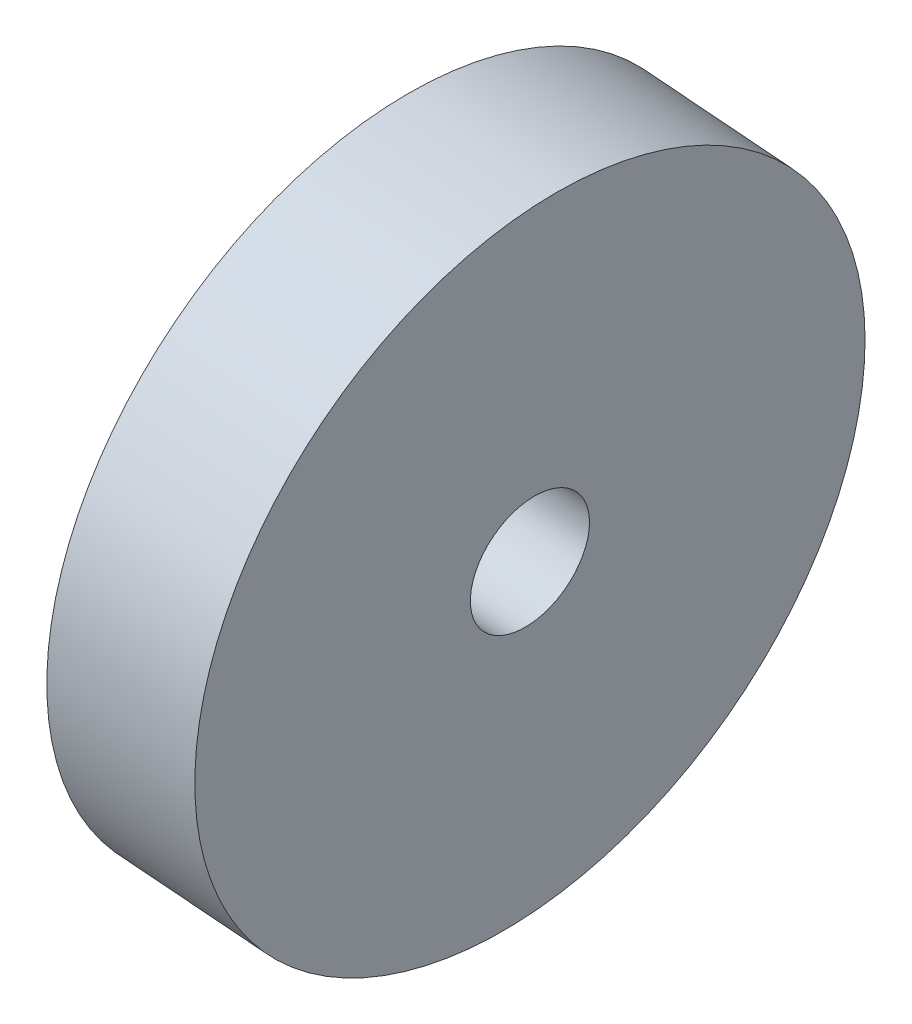
SolidWorks part; units mm, degrees
ref_plane "Front Plane" through (0, 0, 0) normal (0, 0, 1) x (1, 0, 0)
ref_plane "Top Plane" through (0, 0, 0) normal (0, 1, 0) x (1, 0, 0)
ref_plane "Right Plane" through (0, 0, 0) normal (1, 0, 0) x (0, 0, -1)
sketch "Sketch1" plane through (234.2789, -18.689, 0) normal (0.9968, -0.0795, 0) x (0, 0, -1)
  circle A1 centre (-43.1743, 8.5503) radius 14.2875
  dimension "D1" = 28.575
extrude "Boss-Extrude1" add sketch "Sketch1" against normal blind 6.35
sketch "Sketch2" plane through (234.2789, -18.689, 0) normal (0.9968, -0.0795, 0) x (0, 0, -1)
  circle A0 centre (-43.1743, 8.5503) radius 2.54
extrude "Cut-Extrude1" cut sketch "Sketch2" against normal blind 5.08
